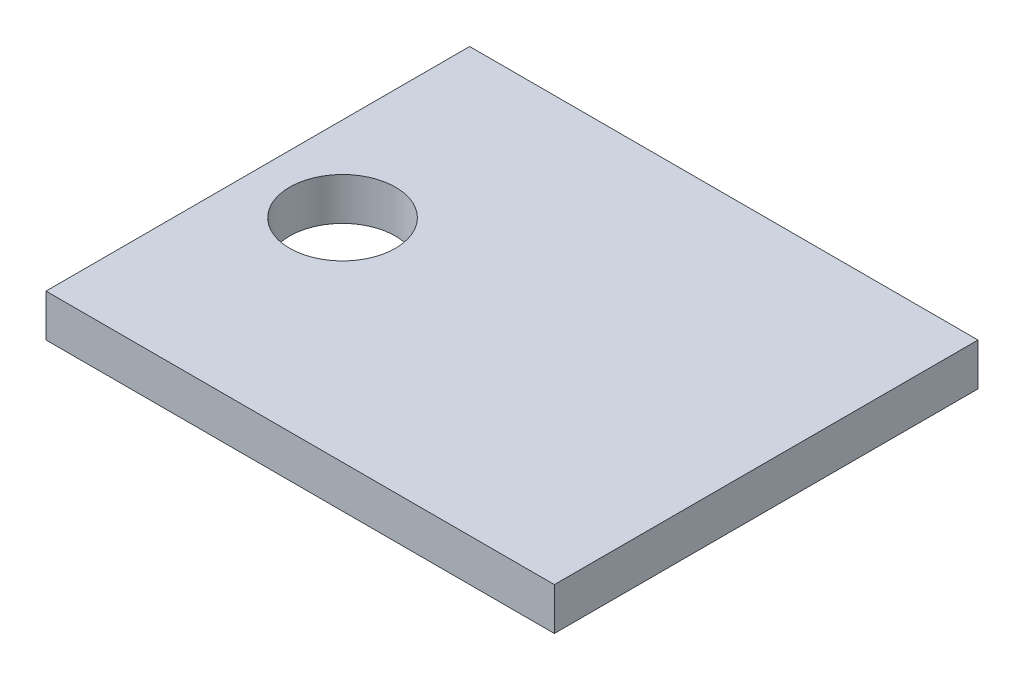
SolidWorks part; units mm, degrees
ref_plane "Front Plane" through (0, 0, 0) normal (0, 0, 1) x (1, 0, 0)
ref_plane "Top Plane" through (0, 0, 0) normal (0, 1, 0) x (1, 0, 0)
ref_plane "Right Plane" through (0, 0, 0) normal (1, 0, 0) x (0, 0, -1)
sketch "Sketch1" plane through (0, 0, 0) normal (0, 1, 0) x (1, 0, 0)
  line L0 (-60, 0) -> (-40, 0) construction
  line L1 (-60, -50) -> (60, -50)
  line L2 (-60, -50) -> (-60, 50)
  line L3 (-60, 50) -> (60, 50)
  line L4 (60, -50) -> (60, 50)
  line L5 (-60, -50) -> (60, 50) construction
  line L6 (-60, 50) -> (60, -50) construction
  circle A0 centre (-40, 0) radius 12.5
  point P0 (0, 0)
  dimension "D4" = 25
  dimension "D1" = 100
  dimension "D2" = 120
  dimension "D3" = 20
extrude "Boss-Extrude1" add sketch "Sketch1" along normal mid plane 10
